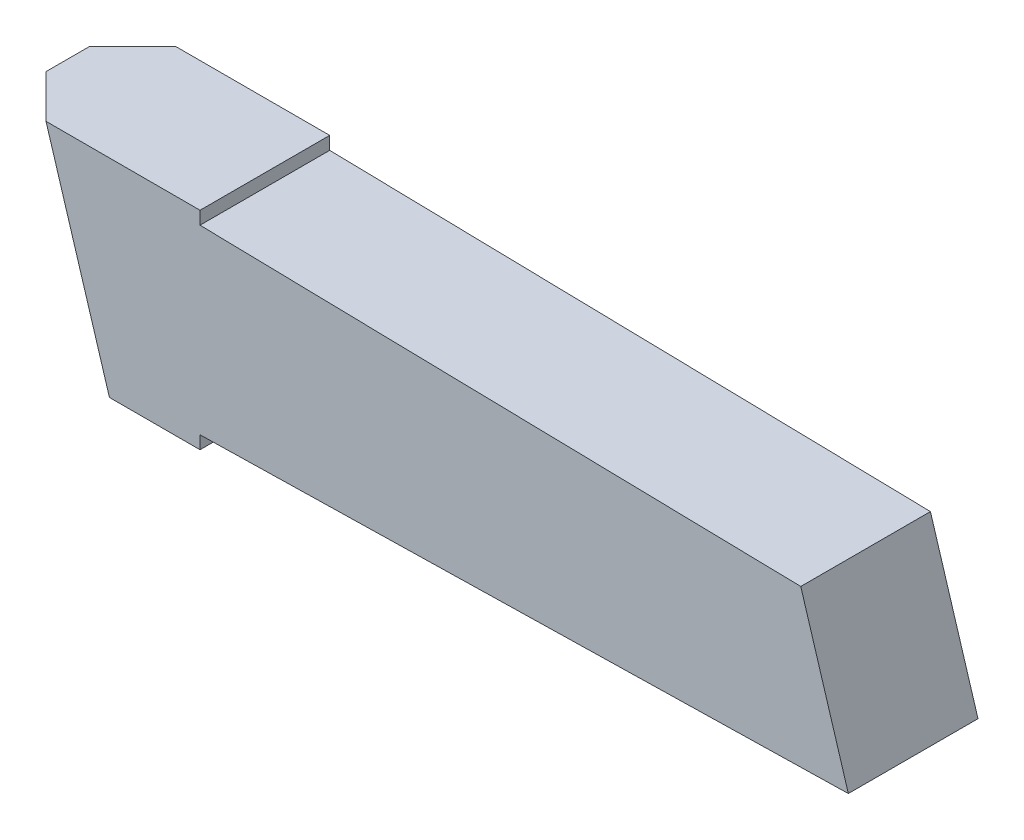
SolidWorks part; units mm, degrees
ref_plane "Frontal" through (0, 0, 0) normal (0, 0, 1) x (1, 0, 0)
ref_plane "Superior" through (0, 0, 0) normal (0, 1, 0) x (1, 0, 0)
ref_plane "Lateral" through (0, 0, 0) normal (1, 0, 0) x (0, 0, -1)
sketch "Sketch1" plane through (0, 0, 0) normal (0, 0, 1) x (1, 0, 0)
  line L0 (-5.1542, -4) -> (-7.6, 4)
  line L1 (-7.6, 4) -> (0, 4)
  line L2 (0, 4) -> (0, 3.5)
  line L3 (0, 3.5) -> (23.1656, 3.019)
  line L4 (23.1656, 3.019) -> (25, -2.981)
  line L5 (0, -3.5) -> (25, -2.981)
  line L6 (0, -3.5) -> (0, -4)
  line L7 (0, -4) -> (-5.1542, -4)
  line L8 (29.072, 0) -> (-11.7306, 0) construction
  line L10 (0, 3.5) -> (0, -3.5) construction
  point P17 (0, 4)
  dimension "D13" = 5.1542
  dimension "D3" = 7.6
  dimension "D2" = 17
  dimension "D4" = 7
  dimension "D5" = 32.6
  dimension "D6" = 6
  dimension "D8" = 8
  dimension "D11" = 17
extrude "Base-Extrude" add sketch "Sketch1" along normal mid plane 5
sketch "Esboço1" plane through (0, 4, 0) normal (0, 1, 0) x (1, 0, 0)
  line L0 (-5.94, -2.5) -> (-7.6, -0.84)
  line L1 (0, -2.5) -> (-7.6, -2.5) construction
  line L2 (-7.6, -2.5) -> (-7.6, 2.5) construction
  line L3 (-7.6, -0.84) -> (-7.6, -2.5)
  line L4 (-7.6, -2.5) -> (-5.94, -2.5)
  line L5 (-5.94, 2.5) -> (-7.6, 0.84)
  line L6 (0, 2.5) -> (-7.6, 2.5) construction
  line L7 (-7.6, 0.84) -> (-7.6, 2.5)
  line L8 (-7.6, 2.5) -> (-5.94, 2.5)
  line L9 (0, 0) -> (-7.6, 0) construction
  line L10 (0, -2.5) -> (0, 2.5) construction
  dimension "D2" = 45
  dimension "D3" = 1.68
extrude "Corte-extrusão1" cut sketch "Esboço1" along direction (0.2924, -0.9563, 0) on the side against the normal blind 10
